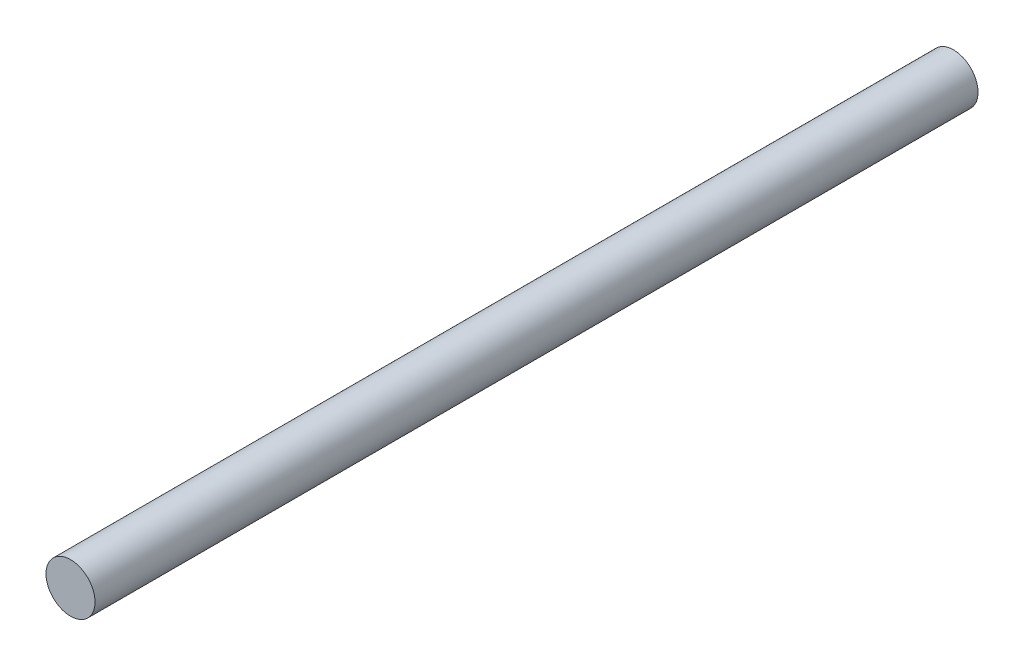
SolidWorks part; units mm, degrees
ref_plane "Alzado" through (0, 0, 0) normal (0, 0, 1) x (1, 0, 0)
ref_plane "Planta" through (0, 0, 0) normal (0, 1, 0) x (1, 0, 0)
ref_plane "Vista lateral" through (0, 0, 0) normal (1, 0, 0) x (0, 0, -1)
sketch "Croquis1" plane through (0, 0, 0) normal (0, 0, 1) x (1, 0, 0)
  circle A0 centre (0, 0) radius 2.5
  dimension "D1" = 5
extrude "Saliente-Extruir1" add sketch "Croquis1" along normal blind 90
